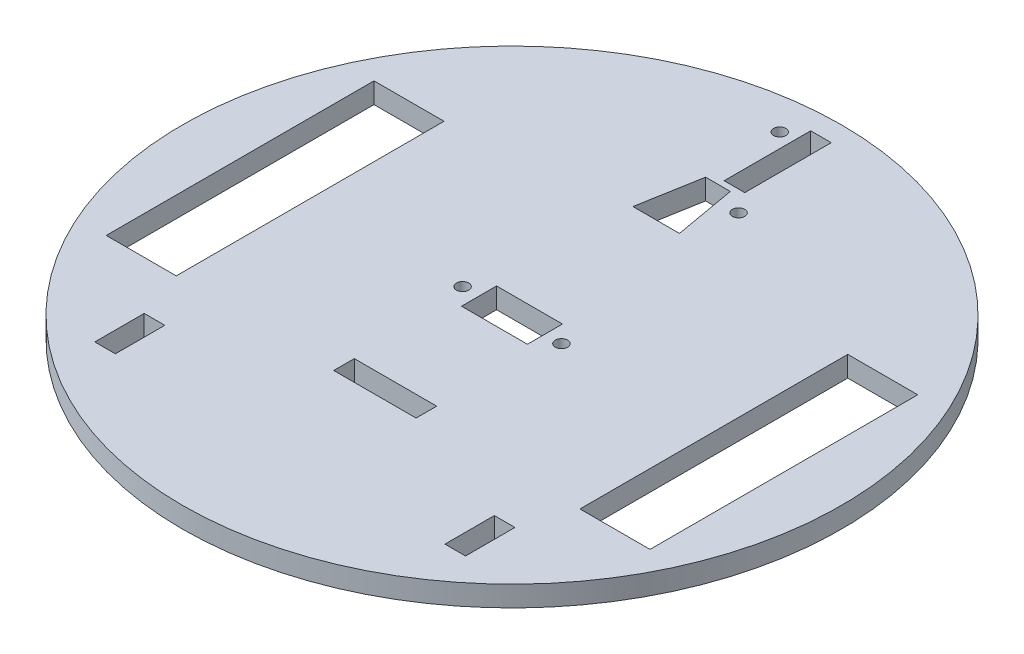
SolidWorks part; units mm, degrees
ref_plane "Front Plane" through (0, 0, 0) normal (0, 0, 1) x (1, 0, 0)
ref_plane "Top Plane" through (0, 0, 0) normal (0, 1, 0) x (1, 0, 0)
ref_plane "Right Plane" through (0, 0, 0) normal (1, 0, 0) x (0, 0, -1)
sketch "Sketch1" plane through (0, 0, 0) normal (0, 1, 0) x (1, 0, 0)
  line L0 (0, 80) -> (0, -94.4249) construction
  line L1 (-49, -32.5) -> (-66, -32.5)
  line L2 (-49, -32.5) -> (-49, 32.5)
  line L3 (-49, 32.5) -> (-66, 32.5)
  line L4 (-66, -32.5) -> (-66, 32.5)
  line L5 (-49, -32.5) -> (-66, 32.5) construction
  line L6 (-49, 32.5) -> (-66, -32.5) construction
  line L7 (49, 32.5) -> (66, -32.5) construction
  line L8 (49, -32.5) -> (66, 32.5) construction
  line L9 (66, -32.5) -> (66, 32.5)
  line L10 (49, 32.5) -> (66, 32.5)
  line L11 (49, -32.5) -> (49, 32.5)
  line L12 (49, -32.5) -> (66, -32.5)
  line L22 (10, 45) -> (-10, 45) construction
  line L23 (10, 45) -> (10, 75) construction
  line L24 (10, 75) -> (-10, 75) construction
  line L25 (-10, 45) -> (-10, 75) construction
  line L29 (-2.5, 47.9262) -> (-2.5, 29.5017) construction
  line L30 (2.5, 54) -> (-2.5, 54)
  line L31 (2.5, 54) -> (2.5, 75)
  line L32 (2.5, 75) -> (-2.5, 75)
  line L33 (-2.5, 54) -> (-2.5, 75)
  line L34 (2.5, 54) -> (-2.5, 75) construction
  line L35 (2.5, 75) -> (-2.5, 54) construction
  line L36 (-5.5, 52.5) -> (0.5, 52.5)
  line L37 (0.5, 52.5) -> (3.1449, 37.5)
  line L38 (3.1449, 37.5) -> (-8.1449, 37.5)
  line L39 (-5.5, 52.5) -> (-8.1449, 37.5)
  line L40 (45, -44.282) -> (45, -56.282)
  line L41 (-40, -33.282) -> (40, -33.282) construction
  line L42 (-40, -33.282) -> (-40, -67.282) construction
  line L43 (-40, -67.282) -> (40, -67.282) construction
  line L44 (40, -33.282) -> (40, -67.282) construction
  line L45 (-40, -44.282) -> (-45, -44.282)
  line L46 (-40, -44.282) -> (-40, -56.282)
  line L47 (-40, -56.282) -> (-45, -56.282)
  line L48 (-45, -44.282) -> (-45, -56.282)
  line L49 (-10, -28.282) -> (10, -28.282)
  line L50 (-10, -28.282) -> (-10, -33.282)
  line L51 (-10, -33.282) -> (10, -33.282)
  line L52 (10, -28.282) -> (10, -33.282)
  line L53 (40, -56.282) -> (45, -56.282)
  line L54 (40, -44.282) -> (40, -56.282)
  line L55 (40, -44.282) -> (45, -44.282)
  circle A0 centre (0, 0) radius 80
  circle A4 centre (-6, 71) radius 1.5
  circle A6 centre (6, 49) radius 1.5
  point P3 (-57.5, 0)
  point P15 (-80, 0)
  point P17 (0, 80)
  point P21 (0, 45)
  point P32 (-2.5, 37.5)
  point P33 (-2.5, 52.5)
  point P37 (0, 64.5)
  point P42 (0, -33.282)
  point P43 (-40, -69.282)
  point P52 (-40, -50.282)
  point P53 (-40, -50.282)
  point P54 (0, -33.282)
  dimension "D1" = 160
  dimension "D6" = 30
  dimension "D9" = 4
  dimension "D7" = 3
  dimension "D2" = 17
  dimension "D3" = 14
  dimension "D4" = 65
  dimension "D5" = 20
  dimension "D8" = 4
  dimension "D10" = 4
  dimension "D11" = 4
  dimension "D12" = 5
  dimension "D13" = 6
  dimension "D14" = 2.5
  dimension "D15" = 10
  dimension "D16" = 7.5
  dimension "D17" = 15
  dimension "D18" = 5
  dimension "D19" = 21
  dimension "D20" = 80
  dimension "D21" = 34
  dimension "D22" = 2
  dimension "D23" = 12
  dimension "D24" = 20
  dimension "D25" = 5
extrude "Boss-Extrude1" add sketch "Sketch1" along normal blind 5
sketch "Sketch2" plane through (0, 5, 0) normal (0, 1, 0) x (1, 0, 0)
  line L0 (8, -4.25) -> (-8, -4.25)
  line L1 (8, -4.25) -> (8, 4.25)
  line L2 (8, 4.25) -> (-8, 4.25)
  line L3 (-8, -4.25) -> (-8, 4.25)
  line L4 (8, -4.25) -> (-8, 4.25) construction
  line L5 (8, 4.25) -> (-8, -4.25) construction
  circle A0 centre (-12, 0) radius 1.5
  circle A1 centre (12, 0) radius 1.5
  point P8 (0, 0)
  dimension "D3" = 3
  dimension "D1" = 16
  dimension "D2" = 8.5
  dimension "D4" = 12
  dimension "D5" = 12
extrude "safety_link" cut sketch "Sketch2" against normal blind 10
